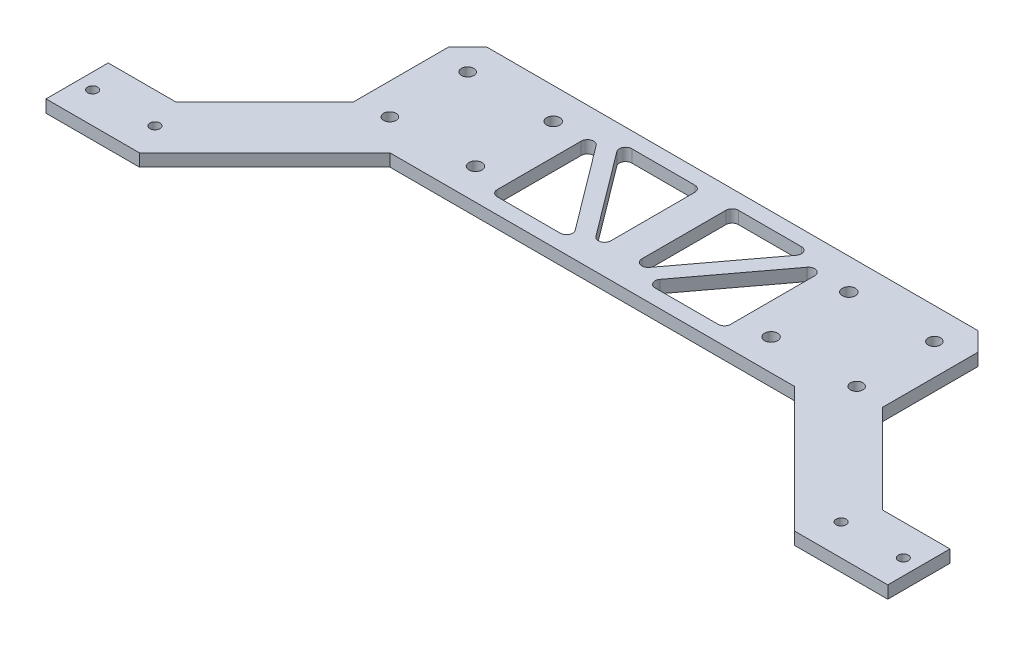
SolidWorks part; units mm, degrees
ref_plane "前视基准面" through (0, 0, 0) normal (0, 0, 1) x (1, 0, 0)
ref_plane "上视基准面" through (0, 0, 0) normal (0, 1, 0) x (1, 0, 0)
ref_plane "右视基准面" through (0, 0, 0) normal (1, 0, 0) x (0, 0, -1)
other "Configuration Table"
sketch "草图1" plane through (0, 0, 0) normal (0, 1, 0) x (1, 0, 0)
  line L0 (85, 45) -> (85, 0) construction
  line L1 (0, 0) -> (170, 0)
  line L2 (0, 0) -> (0, 45)
  line L3 (0, 45) -> (170, 45)
  line L4 (170, 0) -> (170, 45)
  line L5 (10, 35) -> (37.5, 35) construction
  circle A0 centre (10, 35) radius 2
  circle A1 centre (10, 10) radius 2
  circle A2 centre (160, 10) radius 2
  circle A3 centre (160, 35) radius 2
  circle A4 centre (37.5, 35) radius 2.1
  circle A5 centre (37.5, 10) radius 2.1
  circle A6 centre (132.5, 10) radius 2.1
  circle A7 centre (132.5, 35) radius 2.1
  dimension "D2" = 25
  dimension "D4" = 25
  dimension "D5" = 4.2
  dimension "D6" = 4
  dimension "D7" = 10
  dimension "D8" = 95
  dimension "D9" = 10
  dimension "D10" = 10
  dimension "D11" = 150
  dimension "D1" = 2
  dimension "D3" = 2
extrude "凸台-拉伸1" add sketch "草图1" along normal blind 4
sketch "草图2" plane through (0, 0, 0) normal (0, 1, 0) x (1, 0, 0)
  line L0 (170, 8.2843) -> (198.5343, -20.25)
  line L1 (170, 0) -> (170, 45) construction
  line L3 (190.25, -40.25) -> (150, 0)
  line L4 (0, 0) -> (170, 0) construction
  line L5 (150, 0) -> (170, 0)
  line L6 (170, 0) -> (170, 8.2843)
  line L9 (198.5343, -20.25) -> (220.25, -20.25)
  line L11 (0, 45) -> (170, 45) construction
  line L13 (220.25, -20.25) -> (220.25, -40.25)
  line L15 (220.25, -40.25) -> (190.25, -40.25)
  line L17 (85, 45) -> (85, -83.1478) construction
  line L18 (-50.25, -40.25) -> (-20.25, -40.25)
  line L19 (-50.25, -20.25) -> (-50.25, -40.25)
  line L20 (-28.5343, -20.25) -> (-50.25, -20.25)
  line L21 (0, 0) -> (0, 8.2843)
  line L22 (20, 0) -> (0, 0)
  line L23 (-20.25, -40.25) -> (20, 0)
  line L24 (0, 8.2843) -> (-28.5343, -20.25)
  dimension "D1" = 20
  dimension "D2" = 45
  dimension "D3" = 40.25
  dimension "D4" = 36.7157
  dimension "D5" = 30
  dimension "D6" = 20
  dimension "D7" = 135
extrude "凸台-拉伸2" add sketch "草图2" along normal blind 4
sketch "草图4" plane through (0, 4, 0) normal (0, 1, 0) x (1, 0, 0)
  line L0 (0, 38.9095) -> (6, 45)
  line L2 (0, 45) -> (0, 38.9095)
  line L4 (6, 45) -> (0, 45)
  line L6 (170, 39) -> (164, 45)
  line L7 (164, 45) -> (170, 45)
  line L8 (170, 45) -> (170, 39)
  line L9 (0, 8.2843) -> (0, 45) construction
  line L10 (-50.6654, 38.9095) -> (220.6654, 38.9095) construction
  dimension "D1" = 45
  dimension "D2" = 6
  dimension "D3" = 6
extrude "切除-拉伸1" cut sketch "草图4" against normal blind 4
sketch "草图5" plane through (0, 0, 0) normal (0, -1, 0) x (1, 0, 0)
  line L0 (47.5, -5) -> (47.5, -40)
  line L1 (47.5, -40) -> (73.75, -5)
  line L2 (73.75, -5) -> (47.5, -5)
  line L3 (53.75, -40) -> (80, -5)
  line L4 (80, -5) -> (80, -40)
  line L5 (80, -40) -> (53.75, -40)
  line L6 (90, -5) -> (90, -40)
  line L7 (90, -40) -> (116.25, -40)
  line L8 (116.25, -40) -> (90, -5)
  line L9 (96.25, -5) -> (122.5, -5)
  line L10 (122.5, -5) -> (122.5, -40)
  line L11 (122.5, -40) -> (96.25, -5)
  line L12 (85, -45) -> (85, 0) construction
  line L13 (6, -45) -> (164, -45) construction
  line L14 (20, 0) -> (150, 0) construction
  line L15 (170, -8.2843) -> (170, -39) construction
  line L16 (0, -8.2843) -> (0, -38.9095) construction
  dimension "D1" = 5
  dimension "D2" = 5
  dimension "D3" = 5
  dimension "D4" = 5
  dimension "D5" = 5
  dimension "D6" = 5
  dimension "D7" = 47.5
  dimension "D8" = 47.5
extrude "切除-拉伸2" cut sketch "草图5" against normal up to surface (4 mm away) up to face at (85, 4, 3.5951)
fillet "圆角1" radius 2 12 edges at (122.5, 2, -40) (96.25, 2, -5) (122.5, 2, -5) (116.25, 2, -40) (90, 2, -40) (90, 2, -5) (80, 2, -40) (53.75, 2, -40) (80, 2, -5) (73.75, 2, -5) (47.5, 2, -40) (47.5, 2, -5)
sketch "草图6" plane through (0, 0, 0) normal (0, -1, 0) x (1, 0, 0)
  line L0 (-50.25, 30.25) -> (-10.25, 30.25) construction
  line L1 (-50.25, 20.25) -> (-50.25, 40.25) construction
  line L2 (-20.25, 40.25) -> (20, 0) construction
  line L3 (85, -45) -> (85, 0) construction
  line L4 (6, -45) -> (164, -45) construction
  line L6 (20, 0) -> (150, 0) construction
  line L7 (220.25, 30.25) -> (180.25, 30.25) construction
  circle A0 centre (-45.25, 30.25) radius 1.6
  circle A1 centre (-25.25, 30.25) radius 1.6
  circle A2 centre (195.25, 30.25) radius 1.6
  circle A3 centre (215.25, 30.25) radius 1.6
  dimension "D1" = 3.2
  dimension "D2" = 20
  dimension "D3" = 5
extrude "切除-拉伸3" cut sketch "草图6" against normal blind 50
